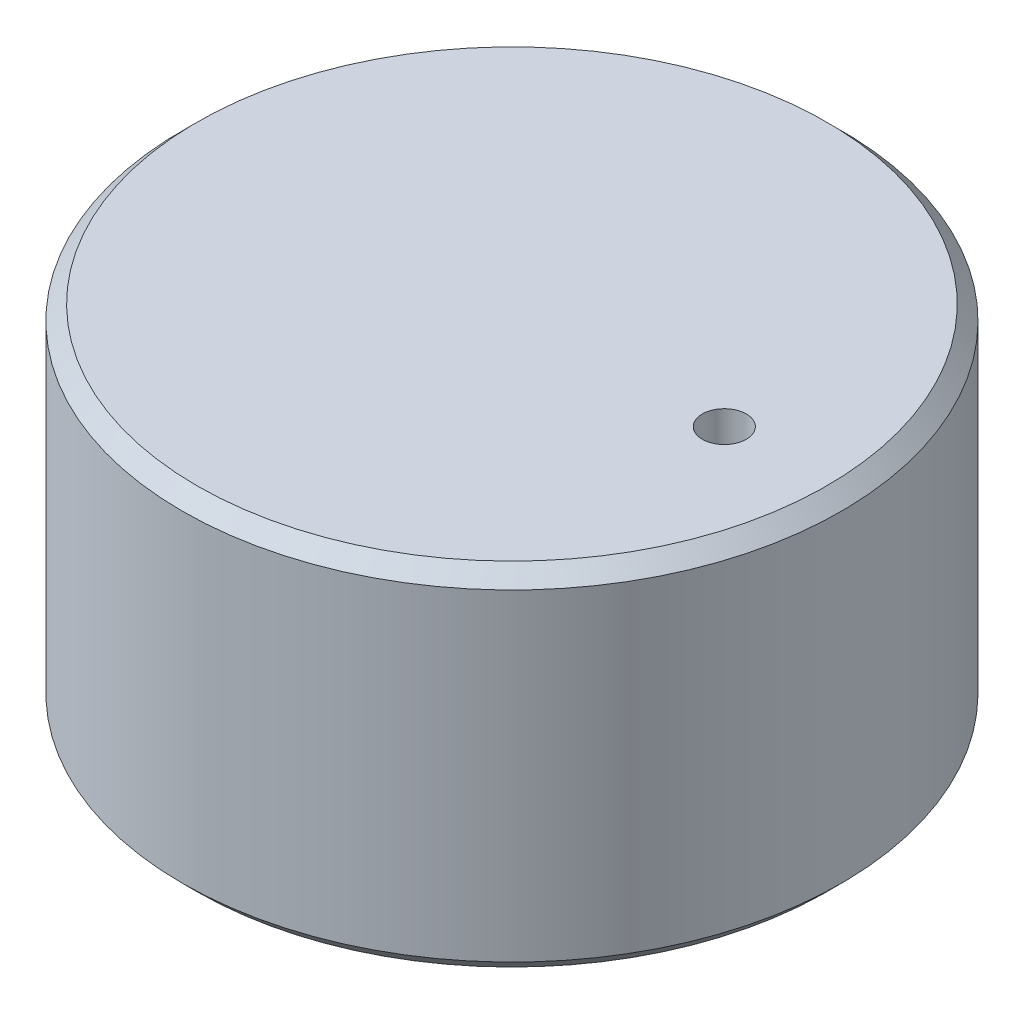
SolidWorks part; units mm, degrees
ref_plane "Front Plane" through (0, 0, 0) normal (0, 0, 1) x (1, 0, 0)
ref_plane "Top Plane" through (0, 0, 0) normal (0, 1, 0) x (1, 0, 0)
ref_plane "Right Plane" through (0, 0, 0) normal (1, 0, 0) x (0, 0, -1)
sketch "Sketch1" plane through (0, 0, 0) normal (0, 1, 0) x (1, 0, 0)
  circle A0 centre (0, 0) radius 22.5
  dimension "D1" = 45
extrude "Boss-Extrude1" add sketch "Sketch1" along normal blind 24
chamfer "Chamfer1" distance 1 angle 45 2 edges at (0, 0, 22.5) (0, 24, 22.5)
sketch "Sketch2" plane through (0, 24, 0) normal (0, 1, 0) x (1, 0, 0)
  circle A0 centre (14.5, 0) radius 1.5
  circle A1 centre (0, 0) radius 22.5 construction
  point P2 (22.5, 0)
  point P3 (0, 0)
  dimension "D1" = 3
  dimension "D2" = 8
extrude "Cut-Extrude1" cut sketch "Sketch2" against normal through all
